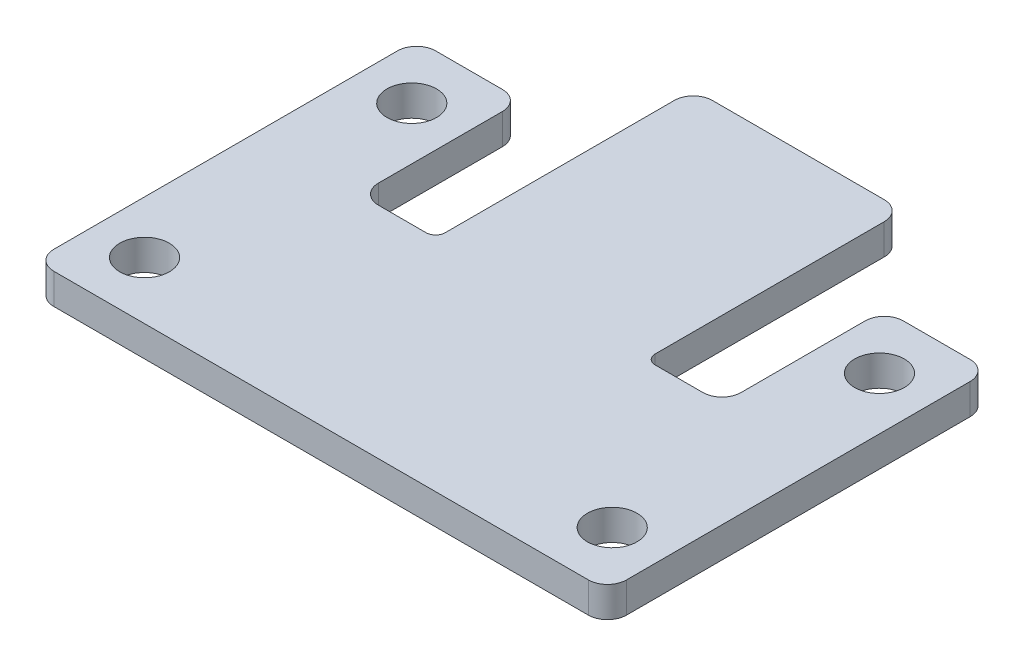
SolidWorks part; units mm, degrees
ref_plane "Front Plane" through (0, 0, 0) normal (0, 0, 1) x (1, 0, 0)
ref_plane "Top Plane" through (0, 0, 0) normal (0, 1, 0) x (1, 0, 0)
ref_plane "Right Plane" through (0, 0, 0) normal (1, 0, 0) x (0, 0, -1)
sketch "Sketch1" plane through (0, 0, 0) normal (0, 1, 0) x (1, 0, 0)
  line L0 (-15, 20) -> (-15, 0)
  line L1 (-15, 0) -> (15, 0)
  line L2 (15, 0) -> (15, 20)
  line L3 (15, 20) -> (9.5, 20)
  line L4 (9.5, 20) -> (9.5, 11.5)
  line L5 (9.5, 11.5) -> (5.5, 11.5)
  line L6 (5.5, 11.5) -> (5.5, 25)
  line L7 (5.5, 25) -> (-5.5, 25)
  line L8 (-5.5, 25) -> (-5.5, 11.5)
  line L9 (-5.5, 11.5) -> (-9.5, 11.5)
  line L10 (-9.5, 11.5) -> (-9.5, 20)
  line L11 (-9.5, 20) -> (-15, 20)
  point P2 (0, 25)
  dimension "D1" = 11
  dimension "D2" = 25
  dimension "D3" = 20
  dimension "D4" = 13.5
  dimension "D5" = 30
  dimension "D6" = 5.5
extrude "Boss-Extrude1" add sketch "Sketch1" along normal blind 1.6
fillet "Fillet1" radius 1 10 edges at (-9.5, 0.8, -20) (-9.5, 0.8, -11.5) (-5.5, 0.8, -25) (5.5, 0.8, -25) (9.5, 0.8, -11.5) (9.5, 0.8, -20) (15, 0.8, 0) (-15, 0.8, 0) (-15, 0.8, -20) (15, 0.8, -20)
sketch "Sketch2" plane through (0, 1.6, 0) normal (0, 1, 0) x (1, 0, 0)
  line L0 (-10.5, 20) -> (-14, 20) construction
  line L1 (0, 25) -> (0, 0) construction
  line L2 (4.5, 25) -> (-4.5, 25) construction
  line L3 (-14, 0) -> (14, 0) construction
  line L4 (-15, 10) -> (15, 10) construction
  line L5 (-15, 19) -> (-15, 1) construction
  line L6 (15, 1) -> (15, 19) construction
  circle A0 centre (-12.25, 17) radius 2.25 construction
  circle A1 centre (-12.25, 3) radius 2.25 construction
  point P0 (-12.25, 20)
  point P1 (-12.25, 17)
  point P16 (-12.25, 3)
  point P17 (12.25, 3)
  point P18 (12.25, 17)
  dimension "D2" = 4.5
  dimension "D3" = 4.5
  dimension "D1" = 3
hole_wizard "M2 Clearance Hole1" positions "Sketch3" profile "Sketch4" hole size "M2" standard "ANSI Metric"
sketch "Sketch3" plane through (0, 1.6, 0) normal (0, 1, 0) x (1, 0, 0)
  point P0 (-12.25, 17)
  point P3 (-12.25, 3)
  point P6 (12.25, 3)
  point P9 (12.25, 17)
sketch "Sketch4" plane through (-12.25, 1.6, -17) normal (1, 0, 0) x (0, 0, 1)
  line L0 (0, 0) -> (0, 2.3811)
  line L1 (0, 2.3811) -> (1.3, 1.6)
  line L2 (1.3, 1.6) -> (1.3, 0)
  line L5 (1.3, 0) -> (0, 0)
  line L10 (0, 2.3811) -> (-1.3, 1.6) construction
  line L11 (0, -6.35) -> (0, 107.95) construction
  dimension "Hole Dia." = 2.6
  dimension "Hole Depth" = 1.6
  dimension "Drill Angle" = 118
fillet "Fillet2" radius 0.5 2 edges at (5.5, 0.8, -11.5) (-5.5, 0.8, -11.5)
